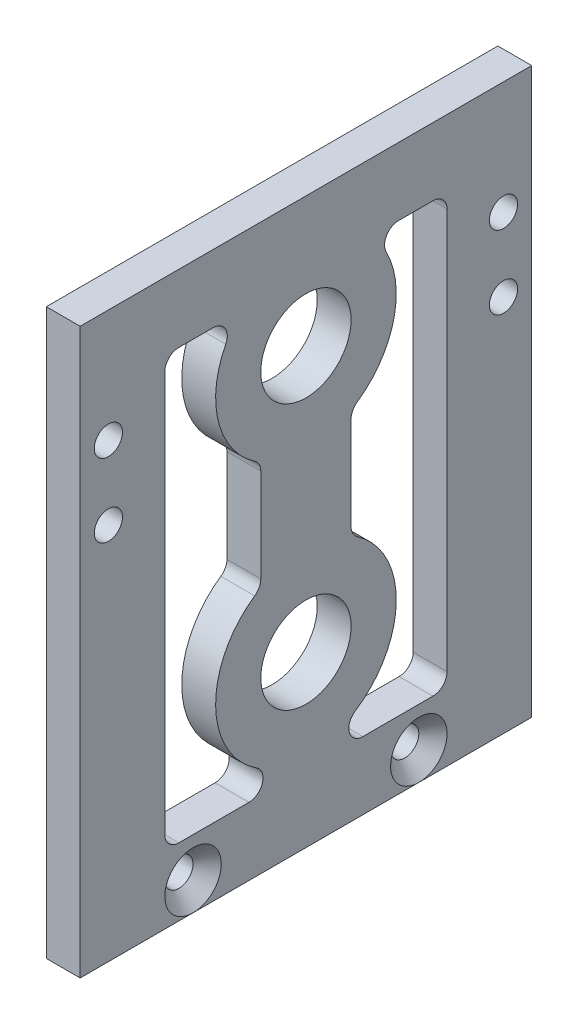
SolidWorks part; units mm, degrees
ref_plane "Plan de face" through (0, 0, 0) normal (0, 0, 1) x (1, 0, 0)
ref_plane "Plan de dessus" through (0, 0, 0) normal (0, 1, 0) x (1, 0, 0)
ref_plane "Plan de droite" through (0, 0, 0) normal (1, 0, 0) x (0, 0, -1)
sketch "Esquisse1" plane through (0, 0, 0) normal (1, 0, 0) x (0, 0, -1)
  line L1 (0, 0) -> (80, 0)
  line L2 (0, 0) -> (0, 100)
  line L3 (0, 100) -> (80, 100)
  line L4 (80, 0) -> (80, 100)
  dimension "D1" = 100
  dimension "D2" = 80
extrude "Extrusion1" add sketch "Esquisse1" along normal blind 6
sketch "Esquisse2" plane through (6, 0, 0) normal (1, 0, 0) x (0, 0, -1)
  line L0 (80, 100) -> (0, 100) construction
  line L1 (0, 100) -> (0, 0) construction
  line L2 (0, 0) -> (80, 0) construction
  line L3 (80, 0) -> (80, 100) construction
  line L4 (17.5, 88) -> (23.5683, 88)
  line L5 (15, 85.5) -> (15, 14.5)
  line L6 (17.5, 12) -> (29.9005, 12)
  line L7 (65, 85.5) -> (65, 14.5)
  line L8 (56.4317, 88) -> (62.5, 88)
  line L9 (50.0995, 12) -> (62.5, 12)
  line L10 (32, 61.7685) -> (32, 45.2315)
  line L12 (48, 61.7685) -> (48, 45.2315)
  circle A0 centre (40, 77) radius 8
  circle A1 centre (40, 30) radius 8
  circle A2 centre (5, 80) radius 2.5
  circle A3 centre (75, 80) radius 2.5
  circle A4 centre (5, 67) radius 2.5
  circle A5 centre (75, 67) radius 2.5
  circle A6 centre (20, 5) radius 2.5
  circle A7 centre (60, 5) radius 2.5
  arc A8 (25.7888, 84.3514) -> (30.9189, 63.8268) centre (40, 77) ccw
  arc A9 (30.9189, 43.1732) -> (31.2653, 16.5946) centre (40, 30) ccw
  arc A10 (17.5, 88) -> (15, 85.5) centre (17.5, 85.5) ccw
  arc A11 (25.7888, 84.3514) -> (23.5683, 88) centre (23.5683, 85.5) ccw
  arc A12 (32, 61.7685) -> (30.9189, 63.8268) centre (29.5, 61.7685) ccw
  arc A13 (30.9189, 43.1732) -> (32, 45.2315) centre (29.5, 45.2315) ccw
  arc A14 (29.9005, 12) -> (31.2653, 16.5946) centre (29.9005, 14.5) ccw
  arc A15 (15, 14.5) -> (17.5, 12) centre (17.5, 14.5) ccw
  arc A16 (48.7347, 16.5946) -> (50.0995, 12) centre (50.0995, 14.5) ccw
  arc A17 (62.5, 12) -> (65, 14.5) centre (62.5, 14.5) ccw
  arc A18 (48, 45.2315) -> (49.0811, 43.1732) centre (50.5, 45.2315) ccw
  arc A19 (49.0811, 63.8268) -> (48, 61.7685) centre (50.5, 61.7685) ccw
  arc A20 (65, 85.5) -> (62.5, 88) centre (62.5, 85.5) ccw
  arc A21 (56.4317, 88) -> (54.2112, 84.3514) centre (56.4317, 85.5) ccw
  arc A22 (49.0811, 63.8268) -> (54.2112, 84.3514) centre (40, 77) ccw
  arc A23 (48.7347, 16.5946) -> (49.0811, 43.1732) centre (40, 30) ccw
  dimension "D1" = 16
  dimension "D2" = 23
  dimension "D3" = 40
  dimension "D4" = 5
  dimension "D5" = 5
  dimension "D6" = 20
  dimension "D7" = 5
  dimension "D8" = 5
  dimension "D9" = 20
  dimension "D16" = 32
  dimension "D17" = 32
  dimension "D18" = 5
  dimension "D19" = 5
  dimension "D20" = 5
  dimension "D21" = 5
  dimension "D22" = 5
  dimension "D23" = 5
  dimension "D24" = 5
  dimension "D25" = 5
  dimension "D26" = 5
  dimension "D27" = 5
  dimension "D28" = 5
  dimension "D29" = 5
  dimension "D10" = 12
  dimension "D11" = 15
  dimension "D12" = 15
  dimension "D13" = 12
  dimension "D14" = 8
  dimension "D15" = 8
extrude "Extrusion3" cut sketch "Esquisse2" against normal through all
chamfer "Chanfrein1" distance 2.5 angle 45 2 edges at (6, 5, -57.5) (6, 5, -22.5)
